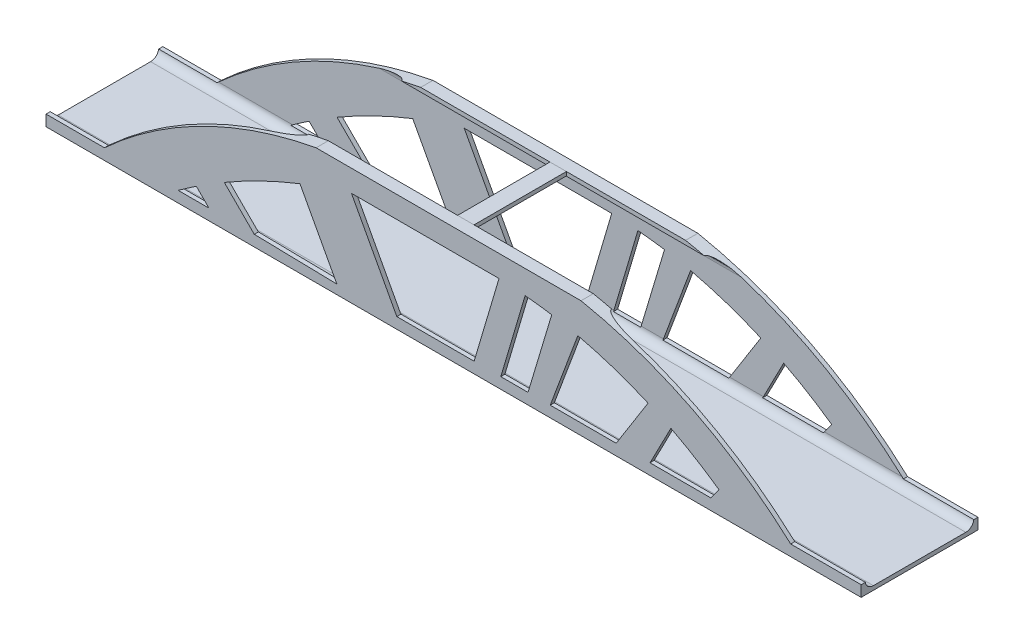
SolidWorks part; units mm, degrees
material "AISI 304"
ref_plane "Front Plane" through (0, 0, 0) normal (0, 0, 1) x (1, 0, 0)
ref_plane "Top Plane" through (0, 0, 0) normal (0, 1, 0) x (1, 0, 0)
ref_plane "Right Plane" through (0, 0, 0) normal (1, 0, 0) x (0, 0, -1)
sketch "Sketch1" plane through (0, 0, 0) normal (0, 0, 1) x (1, 0, 0)
  line L0 (-7500, -872.4997) -> (-7500, -1074.9998)
  line L1 (-7500, -1074.9998) -> (7499.9998, -1075.0003)
  line L2 (7499.9998, -1075.0003) -> (7500, -872.4997)
  line L3 (7500, -872.4997) -> (6203.2871, -872.4997)
  line L4 (-2530, 1075.0003) -> (2344.5999, 1075.0003)
  line L5 (-4219.0082, -320.781) -> (-3667.2896, -872.4997)
  line L6 (-2826.8354, 353.9013) -> (-2147.6328, -905.5435)
  line L7 (3614.8566, -872.4997) -> (4731.8521, -872.4997)
  line L8 (3999.0056, -129.7975) -> (3614.8566, -872.4997)
  line L9 (4731.8521, -872.4997) -> (4883.3486, -666.0055)
  line L10 (4731.8521, -872.4997) -> (3614.8566, -872.4997)
  line L11 (3579.0542, 60.4015) -> (2991.9204, -872.4997)
  line L12 (2991.9204, -872.4997) -> (3579.0542, 60.4015)
  line L13 (2991.9204, -872.4997) -> (1778.1442, -872.4997)
  line L14 (1778.1442, -872.4997) -> (2286.3413, 490.443)
  line L15 (-4501.2302, -872.4997) -> (-4733.1096, -640.6202)
  line L16 (-4501.2302, -872.4997) -> (-5067.7062, -872.4997)
  line L17 (378.2544, -872.4997) -> (-1044.6097, -872.4997)
  line L18 (-1879.1568, 675.0003) -> (-1044.6097, -872.4997)
  line L19 (-1879.1568, 675.0003) -> (760.0858, 675.0003)
  line L20 (835.0137, 672.9232) -> (378.2544, -872.4997)
  line L21 (1806.1551, 582.4787) -> (1369.9859, -872.4997)
  line L22 (1369.9859, -872.4997) -> (868.7399, -872.4997)
  line L23 (868.7399, -872.4997) -> (1316.3032, 641.8091)
  line L24 (-2147.6328, -905.5435) -> (-3667.2896, -872.4997)
  line L25 (-6424.8267, -872.4997) -> (-7500, -872.4997)
  arc A0 (6203.2871, -872.4997) -> (2344.5999, 1075.0003) centre (784.167, -6813.2328) ccw
  arc A1 (-2530, 1075.0003) -> (-6424.8267, -872.4997) centre (-1100.8189, -6651.638) ccw
  arc A2 (-2826.8354, 353.9013) -> (-4219.0082, -320.781) centre (926.5868, -9164.7759) ccw
  arc A3 (4883.3486, -666.0055) -> (3999.0056, -129.7975) centre (528.8225, -6850.3669) ccw
  arc A4 (3579.0542, 60.4015) -> (2286.3413, 490.443) centre (554.8872, -6872.3207) ccw
  arc A5 (-4733.1096, -640.6202) -> (-5067.7062, -872.4997) centre (926.5868, -9164.7759) ccw
  arc A6 (835.0137, 672.9232) -> (760.0858, 675.0003) centre (587.957, -6886.6526) ccw
  arc A7 (1806.1551, 582.4787) -> (1316.3032, 641.8091) centre (652.2629, -6892.5969) ccw
  point P15 (3614.8566, -872.4997)
  point P22 (2286.3413, 490.443)
  point P23 (3622.4711, 60.4015)
  point P44 (0, 0)
  point P45 (2966.6052, -872.4997)
  point P46 (1778.1442, -872.4997)
  point P47 (1369.9859, -872.4997)
  point P48 (1806.1551, 582.4787)
  point P49 (3999.0056, -129.7975)
  point P50 (3622.4711, -846.0753)
  point P51 (4883.3486, -666.0055)
  point P52 (4731.8521, -846.0753)
extrude "Boss-Extrude1" add sketch "Sketch1" along normal mid plane 2150 contours L4 A1 L25 L0 L1 L2 L3 A0 A7 L21 L22 L23 A6 L20 L17 L18 L19 A5 L15 L16 A4 L11 L13 L14 A3 L9 L7 L8 A2 L6 L24 L5
sketch "Sketch2" plane through (0, 0, 0) normal (1, 0, 0) x (0, 0, -1)
  line L0 (-1075, -872.4997) -> (1075, -872.4997) construction
  line L1 (-1075, -1075.0003) -> (1075, -1075.0003) construction
  line L2 (1075, -872.4997) -> (1075, 1075.0003) construction
  line L3 (-1075, 1075.0003) -> (1075, 1075.0003) construction
  line L4 (-1075, 1075.0003) -> (-1075, -872.4997) construction
  line L5 (-1075, -872.4997) -> (-998.3029, -872.4997)
  line L6 (-1075, -1075.0003) -> (1075, -1075.0003)
  line L7 (1075, -872.4997) -> (1075, 1075.0003)
  line L8 (-1075, 1075.0003) -> (1075, 1075.0003)
  line L9 (-1075, 1075.0003) -> (-1075, -872.4997)
  line L10 (-850, 1000) -> (-850, 1075.0003)
  line L11 (-850, -1000) -> (850, -1000)
  line L12 (-1000, -850) -> (-1000, 850)
  line L14 (1000, -850) -> (1000, 850)
  line L15 (-1000, -1000) -> (-956.066, -956.066) construction
  line L16 (-1000, 1000) -> (-956.066, 956.066) construction
  line L17 (-850, 1075.0003) -> (850, 1075.0003)
  line L18 (850, 1075.0003) -> (850, 1000)
  line L19 (956.066, -956.066) -> (1000, -1000) construction
  line L20 (956.066, 956.066) -> (1000, 1000) construction
  line L21 (998.3029, -872.4997) -> (1075, -872.4997)
  arc A0 (-1000, 850) -> (-850, 1000) centre (-850, 850) cw
  arc A1 (850, 1000) -> (1000, 850) centre (850, 850) cw
  arc A2 (850, -1000) -> (1000, -850) centre (850, -850) ccw
  arc A3 (-850, -1000) -> (-1000, -850) centre (-850, -850) cw
  point P4 (0, 0)
  dimension "D3" = 150
  dimension "D1" = 2000
  dimension "D2" = 2000
extrude "Cut-Extrude1" cut sketch "Sketch2" against normal through all both and the other way through all contours A3 L11 A2 L14 A1 L18 L8 L10 A0 L12
sketch "Sketch3" plane through (0, -1075, 0) normal (0, -1, 0) x (1, 0, 0)
  line L0 (-6000, 1075) -> (-6000, -1075.0062)
  line L1 (-6000, -1075.0062) -> (5999.9998, -1075)
  line L2 (5999.9998, -1075) -> (5999.9998, 1075)
  line L4 (-7500, -1075) -> (7499.9998, -1075)
  line L5 (7499.9998, -1075) -> (7499.9998, 1075)
  line L6 (7499.9998, 1075) -> (-7500, 1075)
  line L7 (-7500, 1075) -> (-7500, -1075)
  line L8 (-7500, -1075) -> (7499.9998, -1075)
  line L9 (7499.9998, -1075) -> (7499.9998, 1075)
  line L10 (7499.9998, 1075) -> (-7500, 1075)
  line L11 (-7500, 1075) -> (-7500, -1075)
  point P11 (0, 0)
  point P12 (-6015.0002, -1087.3857)
  dimension "D2" = 1500
  dimension "D3" = 1500
  dimension "D1" = 0
split line "Split Line1"
ref_plane "Plane1" through (0, 1075, 0) normal (0, 1, 0) x (1, 0, 0)
sketch "Sketch5" plane through (0, 1075, 0) normal (0, 1, 0) x (1, 0, 0)
  line L0 (-2530, -1075) -> (2344.5999, -1075) construction
  line L1 (-2530, 1075) -> (2344.5999, 1075) construction
  line L2 (-151.1919, -1075) -> (151.1919, -1075)
  line L3 (-151.1919, 1075) -> (151.1919, 1075)
  line L4 (-151.1919, -1075) -> (-151.1919, 1075)
  line L5 (-151.1919, -1075) -> (151.1919, -1075)
  line L6 (-151.1919, 1075) -> (151.1919, 1075)
  line L7 (151.1919, -1075) -> (151.1919, 1075)
  point P5 (0, 0)
extrude "Boss-Extrude2" add sketch "Sketch5" against normal blind 70 contours L2 L7 L3 L4
